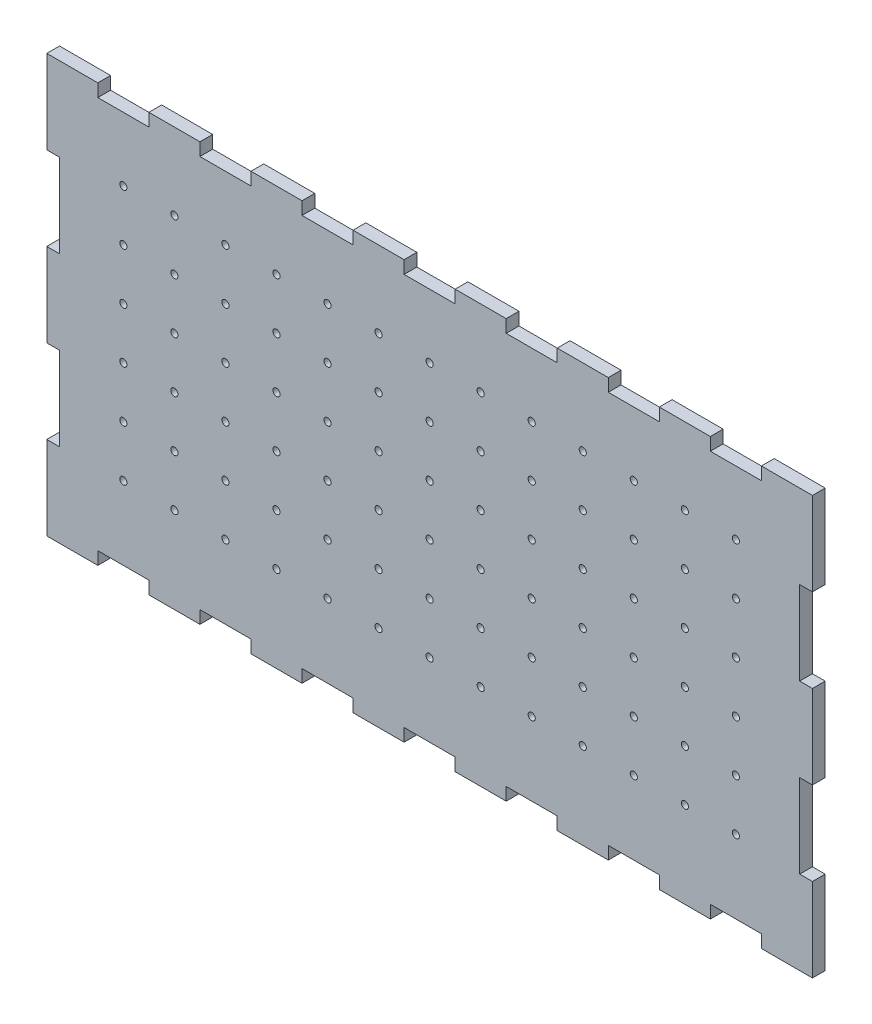
SolidWorks part; units mm, degrees
ref_plane "Front Plane" through (0, 0, 0) normal (0, 0, 1) x (1, 0, 0)
ref_plane "Top Plane" through (0, 0, 0) normal (0, 1, 0) x (1, 0, 0)
ref_plane "Right Plane" through (0, 0, 0) normal (1, 0, 0) x (0, 0, -1)
sketch "Sketch1" plane through (0, 0, 0) normal (0, 0, 1) x (1, 0, 0)
  line L1 (-190.5, -103.9813) -> (190.5, -103.9813)
  line L2 (-190.5, -103.9813) -> (-190.5, 103.9813)
  line L3 (-190.5, 103.9813) -> (190.5, 103.9813)
  line L4 (190.5, -103.9813) -> (190.5, 103.9813)
  line L5 (-190.5, -103.9813) -> (190.5, 103.9813) construction
  line L6 (-190.5, 103.9813) -> (190.5, -103.9813) construction
  point P0 (0, 0)
  dimension "D1" = 381
  dimension "D2" = 207.9625
extrude "Boss-Extrude1" add sketch "Sketch1" along normal blind 6.35
sketch "Sketch2" plane through (0, 0, 6.35) normal (0, 0, 1) x (1, 0, 0)
  line L0 (190.5, 103.9813) -> (-190.5, 103.9813) construction
  line L1 (-165.1, 103.9813) -> (-139.7, 103.9813)
  line L2 (-165.1, 103.9813) -> (-165.1, 97.6313)
  line L3 (-165.1, 97.6313) -> (-139.7, 97.6313)
  line L4 (-139.7, 103.9813) -> (-139.7, 97.6313)
  dimension "D1" = 25.4
  dimension "D2" = 6.35
  dimension "D3" = 25.4
extrude "Cut-Extrude1" cut sketch "Sketch2" against normal blind 6.35
pattern_linear "LPattern1" count 7 spacing 50.8 along (1, 0, 0) of "Cut-Extrude1"
sketch "Sketch3" plane through (0, 0, 6.35) normal (0, 0, 1) x (1, 0, 0)
  line L0 (-190.5, 103.9813) -> (-190.5, -103.9813) construction
  line L1 (-190.5, 62.3888) -> (-184.15, 62.3888)
  line L2 (-190.5, 62.3888) -> (-190.5, 20.7963)
  line L3 (-190.5, 20.7963) -> (-184.15, 20.7963)
  line L4 (-184.15, 62.3888) -> (-184.15, 20.7963)
  line L5 (-165.1, 103.9813) -> (-190.5, 103.9813) construction
  dimension "D1" = 6.35
  dimension "D2" = 41.5925
  dimension "D3" = 41.5925
extrude "Cut-Extrude2" cut sketch "Sketch3" against normal blind 6.35
pattern_linear "LPattern2" count 2 spacing 83.185 along (0, -1, 0) of "Cut-Extrude2"
sketch "Sketch5" plane through (0, 0, 6.35) normal (0, 0, 1) x (1, 0, 0)
  line L0 (-190.5, -103.9813) -> (190.5, -103.9813) construction
  line L1 (-165.1, -103.9813) -> (-139.7, -103.9813)
  line L2 (-165.1, -103.9813) -> (-165.1, -97.6313)
  line L3 (-165.1, -97.6313) -> (-139.7, -97.6313)
  line L4 (-139.7, -103.9813) -> (-139.7, -97.6313)
  dimension "D1" = 6.35
  dimension "D2" = 25.4
  dimension "D3" = 25.4
extrude "Cut-Extrude3" cut sketch "Sketch5" against normal blind 6.35
pattern_linear "LPattern3" count 7 spacing 50.8 along (1, 0, 0) of "Cut-Extrude3"
sketch "Sketch6" plane through (0, 0, 6.35) normal (0, 0, 1) x (1, 0, 0)
  line L0 (190.5, -103.9813) -> (190.5, 103.9813) construction
  line L1 (190.5, 62.3888) -> (184.15, 62.3888)
  line L2 (190.5, 62.3888) -> (190.5, 20.7963)
  line L3 (190.5, 20.7963) -> (184.15, 20.7962)
  line L4 (184.15, 62.3888) -> (184.15, 20.7962)
  dimension "D1" = 6.35
  dimension "D2" = 41.5925
  dimension "D3" = 41.5925
extrude "Cut-Extrude4" cut sketch "Sketch6" against normal blind 6.35
pattern_linear "LPattern4" count 2 spacing 83.185 along (0, -1, 0) of "Cut-Extrude4"
sketch "Sketch7" plane through (0, 0, 6.35) normal (0, 0, 1) x (1, 0, 0)
  line L0 (-165.1, 103.9813) -> (-190.5, 103.9813) construction
  line L1 (-190.5, 103.9813) -> (-190.5, 62.3888) construction
  circle A0 centre (-152.4, 65.8813) radius 1.778
  point P2 (-165.6816, 77.2696)
  point P3 (-166.1367, 74.6737)
  dimension "D1" = 3.556
  dimension "D2" = 38.1
  dimension "D3" = 38.1
extrude "Cut-Extrude5" cut sketch "Sketch7" against normal blind 6.35
pattern_linear "LPattern5" count 13 spacing 25.4 along (1, 0, 0) count 6 spacing 25.4 along (0, -1, 0) of "Cut-Extrude5"
